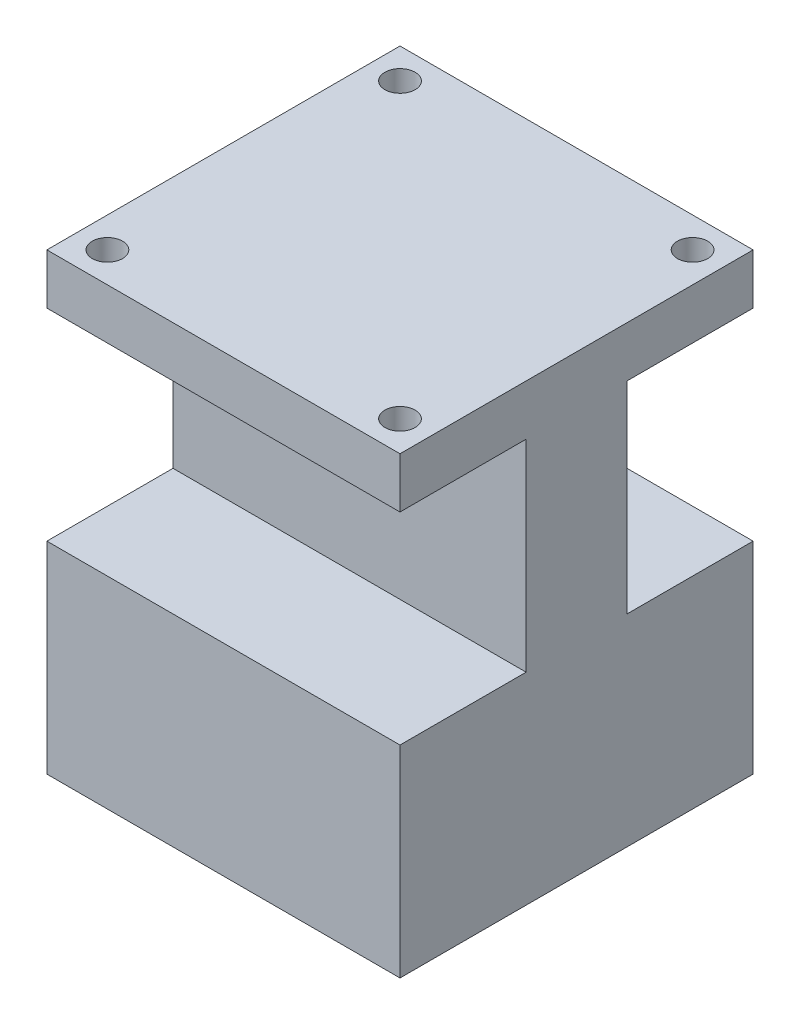
SolidWorks part; units mm, degrees
ref_plane "Front Plane" through (0, 0, 0) normal (0, 0, 1) x (1, 0, 0)
ref_plane "Top Plane" through (0, 0, 0) normal (0, 1, 0) x (1, 0, 0)
ref_plane "Right Plane" through (0, 0, 0) normal (1, 0, 0) x (0, 0, -1)
sketch "Sketch1" plane through (0, 0, 0) normal (0, 1, 0) x (1, 0, 0)
  line L1 (-17.5, 17.5) -> (17.5, 17.5)
  line L2 (-17.5, 17.5) -> (-17.5, -17.5)
  line L3 (-17.5, -17.5) -> (17.5, -17.5)
  line L4 (17.5, 17.5) -> (17.5, -17.5)
  line L5 (-17.5, 17.5) -> (17.5, -17.5) construction
  line L6 (-17.5, -17.5) -> (17.5, 17.5) construction
  point P0 (0, 0)
  dimension "D1" = 35
  dimension "D2" = 35
extrude "Boss-Extrude2" add sketch "Sketch1" along normal blind 20
sketch "Sketch2" plane through (0, 20, 0) normal (0, 1, 0) x (1, 0, 0)
  line L0 (17.5, -17.5) -> (17.5, 17.5) construction
  line L1 (-17.5, 5) -> (17.5, 5)
  line L2 (-17.5, 5) -> (-17.5, -5)
  line L3 (-17.5, -5) -> (17.5, -5)
  line L4 (17.5, 5) -> (17.5, -5)
  line L5 (-17.5, 5) -> (17.5, -5) construction
  line L6 (-17.5, -5) -> (17.5, 5) construction
  point P0 (0, 0)
  dimension "D1" = 10
extrude "Boss-Extrude3" add sketch "Sketch2" along normal blind 20
sketch "Sketch3" plane through (0, 40, 0) normal (0, 1, 0) x (1, 0, 0)
  line L1 (-17.5, 17.5) -> (17.5, 17.5)
  line L2 (-17.5, 17.5) -> (-17.5, -17.5)
  line L3 (-17.5, -17.5) -> (17.5, -17.5)
  line L4 (17.5, 17.5) -> (17.5, -17.5)
extrude "Boss-Extrude4" add sketch "Sketch3" along normal blind 5
sketch "Sketch4" plane through (0, 45, 0) normal (0, 1, 0) x (1, 0, 0)
  line L0 (-17.5, 17.5) -> (-17.5, -17.5) construction
  line L1 (17.5, 17.5) -> (-17.5, 17.5) construction
  line L2 (-3.9192, 0) -> (3.8714, 0) construction
  line L3 (0, 4.2298) -> (0, -4.3254) construction
  circle A0 centre (-14.5, 14.5) radius 1.5
  circle A1 centre (14.5, 14.5) radius 1.5
  circle A2 centre (14.5, -14.5) radius 1.5
  circle A3 centre (-14.5, -14.5) radius 1.5
  dimension "D1" = 3
  dimension "D2" = 3
  dimension "D3" = 3
extrude "Cut-Extrude1" cut sketch "Sketch4" against normal up to next
